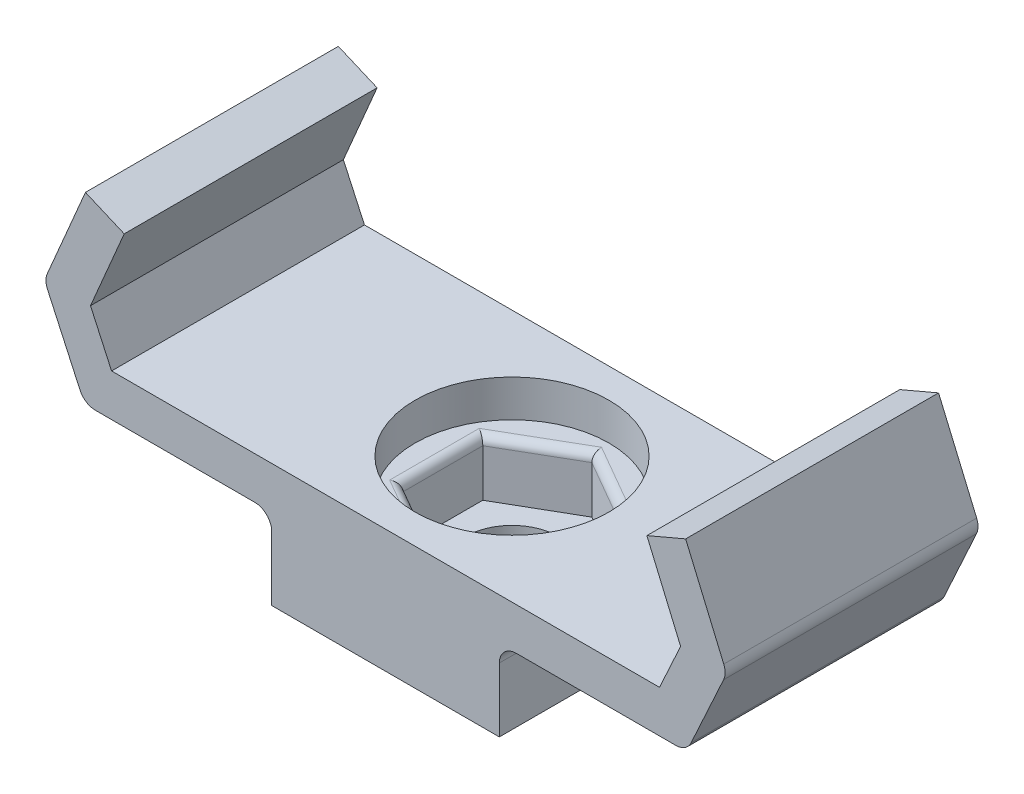
SolidWorks part; units mm, degrees
ref_plane "Front Plane" through (0, 0, 0) normal (0, 0, 1) x (1, 0, 0)
ref_plane "Top Plane" through (0, 0, 0) normal (0, 1, 0) x (1, 0, 0)
ref_plane "Right Plane" through (0, 0, 0) normal (1, 0, 0) x (0, 0, -1)
sketch "Sketch1" plane through (0, 0, 0) normal (0, 0, 1) x (1, 0, 0)
  line L0 (16.25, 0) -> (-16.25, 0)
  line L1 (-16.25, 0) -> (-17.5, 2.7272)
  line L2 (-17.5, 2.7272) -> (-15.5, 7.4187)
  line L3 (0, 0) -> (0, 7.4187) construction
  line L4 (0, 7.4187) -> (-15.5, 7.4187) construction
  line L5 (-15.5, 7.4187) -> (-17.7997, 8.3991)
  line L6 (-17.7997, 8.3991) -> (-20.2333, 2.6905)
  line L7 (-20.2333, 2.6905) -> (-17.8542, -2.5)
  line L8 (-17.8542, -2.5) -> (17.8542, -2.5)
  line L9 (0, -2.5) -> (0, 0)
  line L10 (16.25, 0) -> (17.5, 2.7272)
  line L11 (17.5, 2.7272) -> (15.5, 7.4187)
  line L12 (15.5, 7.4187) -> (17.7997, 8.3991)
  line L13 (17.7997, 8.3991) -> (20.2333, 2.6905)
  line L14 (20.2333, 2.6905) -> (17.8542, -2.5)
  dimension "D1" = 32.5
  dimension "D2" = 35
  dimension "D3" = 31
  dimension "D4" = 3
  dimension "D5" = 5.1
  dimension "D6" = 2.5
  dimension "D7" = 2.5
  dimension "D8" = 2.5
extrude "Boss-Extrude1" add sketch "Sketch1" along normal blind 15 contours L8 L9 L0 L1 L2 L5 L6 L7 | L14 L13 L12 L11 L10 L0 L9 L8
sketch "Sketch4" plane through (0, -2.5, 0) normal (0, -1, 0) x (1, 0, 0)
  line L0 (0, 15) -> (0, 0) construction
  line L1 (-17.8542, 15) -> (17.8542, 15) construction
  line L2 (0, 0) -> (-17.8542, 7.5) construction
  line L3 (-17.8542, 15) -> (-17.8542, 0) construction
  line L4 (-17.8542, 7.5) -> (17.8542, 7.5) construction
  line L5 (17.8542, 15) -> (17.8542, 0) construction
  line L6 (-17.8542, 0) -> (17.8542, 0) construction
  line L7 (6.75, 15) -> (-6.75, 15)
  line L8 (6.75, 15) -> (6.75, 0)
  line L9 (6.75, 0) -> (-6.75, 0)
  line L10 (-6.75, 15) -> (-6.75, 0)
  line L11 (6.75, 15) -> (-6.75, 0) construction
  line L12 (6.75, 0) -> (-6.75, 15) construction
  point P11 (0, 7.5)
  dimension "D1" = 13.5
extrude "Boss-Extrude2" add sketch "Sketch4" along normal blind 4.8
sketch "Sketch5" plane through (0, 0, 0) normal (0, 1, 0) x (1, 0, 0)
  line L0 (0, 0) -> (0, -15) construction
  line L1 (16.25, -15) -> (-16.25, -15) construction
  line L3 (-15.5, -15) -> (-15.5, 0) construction
  line L4 (-15.5, -7.5) -> (15.5, -7.5) construction
  line L5 (15.5, -15) -> (15.5, 0) construction
  line L6 (-4.1, -9.8671) -> (0, -12.2343)
  line L7 (0, -12.2343) -> (4.1, -9.8671)
  line L8 (4.1, -9.8671) -> (4.1, -5.1329)
  line L9 (4.1, -5.1329) -> (0, -2.7657)
  line L10 (0, -2.7657) -> (-4.1, -5.1329)
  line L11 (-4.1, -5.1329) -> (-4.1, -9.8671)
  circle A0 centre (0, -7.5) radius 4.1 construction
  point P12 (0, 0)
  dimension "D1" = 8.2
extrude "Cut-Extrude1" cut sketch "Sketch5" against normal blind 5.5
sketch "Sketch6" plane through (0, 0, 0) normal (0, 1, 0) x (1, 0, 0)
  line L0 (0, -2.7657) -> (0, -12.2343) construction
  circle A0 centre (0, -7.5) radius 5.75
  dimension "D1" = 11.5
extrude "Cut-Extrude2" cut sketch "Sketch6" against normal blind 2.2
sketch "Sketch7" plane through (0, -5.5, 0) normal (0, 1, 0) x (1, 0, 0)
  line L0 (0, -2.7657) -> (0, -12.2343) construction
  circle A0 centre (0, -7.5) radius 2.75
  dimension "D1" = 5.5
extrude "Cut-Extrude3" cut sketch "Sketch7" against normal up to surface (1.8 mm away) up to face at (0, -7.3, 7.5)
fillet "Fillet1" radius 1 6 edges at (-20.2333, 2.6905, 7.5) (20.2333, 2.6905, 7.5) (6.75, -2.5, 7.5) (17.8542, -2.5, 7.5) (-6.75, -2.5, 7.5) (-17.8542, -2.5, 7.5)
fillet "Fillet2" radius 0.5 6 edges at (-4.1, -2.2, 7.5) (-2.05, -2.2, 11.0507) (2.05, -2.2, 11.0507) (4.1, -2.2, 7.5) (2.05, -2.2, 3.9493) (-2.05, -2.2, 3.9493)
